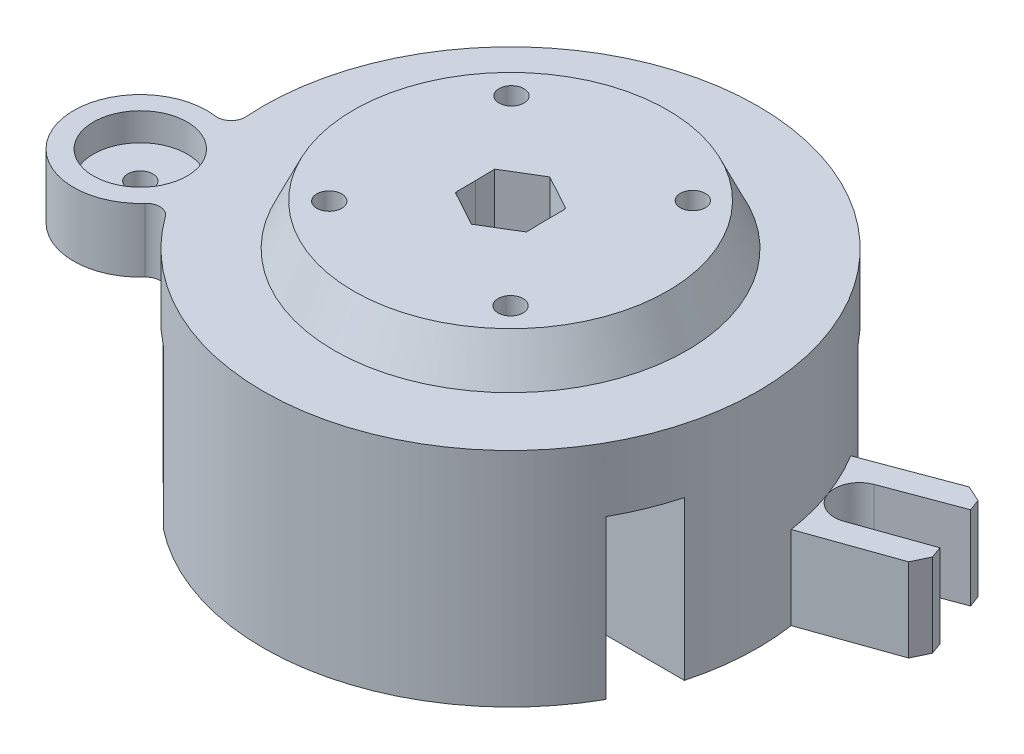
SolidWorks part; units mm, degrees
material "Brass"
ref_plane "Front Plane" through (0, 0, 0) normal (0, 0, 1) x (1, 0, 0)
ref_plane "Top Plane" through (0, 0, 0) normal (0, 1, 0) x (1, 0, 0)
ref_plane "Right Plane" through (0, 0, 0) normal (1, 0, 0) x (0, 0, -1)
sketch "Sketch2" plane through (0, 0, 0) normal (0, 1, 0) x (1, 0, 0)
  line L0 (-400.5493, 0) -> (19626.9166, 0) construction
  line L1 (0, -400.5493) -> (0, 19626.9166) construction
  line L2 (0, 6.35) -> (6.35, 3.4835)
  line L9 (6.35, 3.4835) -> (6.35, -3.4835)
  line L10 (6.35, -3.4835) -> (0, -6.35)
  line L12 (-6.35, -3.4835) -> (0, -6.35)
  line L13 (-6.35, 3.4835) -> (-6.35, -3.4835)
  line L14 (0, 6.35) -> (-6.35, 3.4835)
  circle A0 centre (0, 0) radius 32.258
  circle A1 centre (0, 0) radius 45.212
  point P7 (6.35, 0)
  point P21 (-16.6624, 16.6624)
  point P22 (7.8107, 16.6624)
  point P23 (16.6624, -16.6624)
  point P24 (-16.6624, -16.6624)
  dimension "D1" = 12.7
  dimension "D4" = 64.516
  dimension "D5" = 90.424
  dimension "D2" = 131.41
  dimension "D3" = 12.7
extrude "Boss-Extrude3" add sketch "Sketch2" against normal blind 40.64 contours A1 A0 | A0 L14 L2 L9 L10 L12 L13
sketch "Sketch4" plane through (0, 0, 0) normal (0, 1, 0) x (1, 0, 0)
  circle A0 centre (0, 0) radius 32.258
  dimension "D1" = 64.516
extrude "Boss-Extrude4" add sketch "Sketch4" along normal blind 7.62 draft 25
sketch "Sketch6" plane through (0, -40.64, 0) normal (0, -1, 0) x (-1, 0, 0)
  line L0 (6.35, -3.4835) -> (0, -6.35)
  line L1 (0, -6.35) -> (-6.35, -3.4835)
  line L2 (-6.35, -3.4835) -> (-6.35, 3.4835)
  line L3 (-6.35, 3.4835) -> (0, 6.35)
  line L4 (0, 6.35) -> (6.35, 3.4835)
  line L5 (6.35, 3.4835) -> (6.35, -3.4835)
extrude "Cut-Extrude1" cut sketch "Sketch6" against normal through all
sketch "Sketch7" plane through (0, 7.62, 0) normal (0, 1, 0) x (1, 0, 0)
  line L0 (0, -1000) -> (0, 49000) construction
  line L2 (-1000, 0) -> (49000, 0) construction
  circle A0 centre (-16.4952, 16.6624) radius 2.286
  circle A1 centre (16.6624, 16.6624) radius 2.286
  circle A3 centre (16.6624, -16.6624) radius 2.286
  circle A4 centre (-16.4952, -16.6624) radius 2.286
  point P10 (16.6624, 16.6624)
  point P11 (-16.4952, 16.6624)
  point P12 (16.6624, -16.6624)
  point P13 (-16.4952, -16.6624)
  dimension "D1" = 4.572
  dimension "D2" = 4.572
  dimension "D3" = 4.572
  dimension "D4" = 4.572
extrude "Cut-Extrude2" cut sketch "Sketch7" against normal through all
sketch "Sketch12" plane through (0, 7.62, 0) normal (0, 1, 0) x (1, 0, 0)
  line L0 (0, 0) -> (50000, 0) construction
  line L1 (0, 0) -> (-46984.631, -17101.0072) construction
  circle A0 centre (-49.6458, -18.0696) radius 4.0442
  arc A2 (-47.9736, -5.9928) -> (-40.6021, -26.2461) centre (-49.6458, -18.0696) ccw
  arc A3 (45.212, 0) -> (42.4854, 15.4634) centre (0, 0) ccw
  arc A4 (-36.6585, -26.4628) -> (-40.6021, -26.2461) centre (-38.7179, -27.9495) ccw
  arc A5 (-45.092, -3.2919) -> (-47.9736, -5.9928) centre (-47.6253, -3.4768) cw
  arc A6 (-36.6585, -26.4628) -> (-45.092, -3.2919) centre (0, 0) cw
  arc A7 (-45.212, 0) -> (-45.092, -3.2919) centre (0, 0) ccw
  dimension "D2" = 2.54
  dimension "D1" = 20
  dimension "D3" = 52.832
extrude "Boss-Extrude8" add sketch "Sketch12" against normal blind 11.684 from surface at -7.62 contours A4 A6 A5 A2 A0
sketch "Sketch16" plane through (0, 0, 0) normal (0, 1, 0) x (1, 0, 0)
  circle A0 centre (-49.6458, -18.0696) radius 3.175
sketch "Sketch18" plane through (0, 0, 0) normal (0, 1, 0) x (1, 0, 0)
  circle A1 centre (-49.6458, -18.0696) radius 8.5673
  dimension "D1" = 17.1345
extrude "Cut-Extrude3" cut sketch "Sketch18" against normal blind 5.08
sketch "Sketch19" plane through (0, -5.08, 0) normal (0, 1, 0) x (1, 0, 0)
  circle A1 centre (-49.6458, -18.0696) radius 2.286
  dimension "D1" = 4.572
extrude "Cut-Extrude4" cut sketch "Sketch19" against normal through all
sketch "Sketch20" plane through (0, -40.64, 0) normal (0, -1, 0) x (1, 0, 0)
  line L0 (-5.0709, 1.8457) -> (-46989.7019, 17102.8528) construction
  line L1 (48.3078, -12.7174) -> (61.2371, -17.2959)
  line L2 (61.2371, -17.2959) -> (62.0002, -15.141)
  line L3 (62.0002, -15.141) -> (60.6019, -12.2094)
  line L4 (60.6019, -12.2094) -> (44.7293, -6.5887)
  line L5 (45.1805, -21.3096) -> (58.0279, -26.113)
  line L6 (58.0279, -26.113) -> (57.2273, -28.2543)
  line L7 (57.2273, -28.2543) -> (54.2718, -29.6012)
  line L8 (54.2718, -29.6012) -> (38.4998, -23.7043)
  arc A0 (48.3078, -12.7174) -> (45.1805, -21.3096) centre (46.7817, -17.0271) ccw
  circle A1 centre (0, 0) radius 45.212 construction
  arc A2 (38.4998, -23.7043) -> (44.7293, -6.5887) centre (0, 0) ccw
  circle M5 centre (0, 0) radius 45.212
  dimension "D1" = 4.572
  dimension "D3" = 13.716
  dimension "D2" = 49.784
  dimension "D4" = 1
  dimension "D5" = 45
extrude "Boss-Extrude9" add sketch "Sketch20" against normal blind 15.24 contours A0 L1 L2 L3 L4 M5 | A0 L8 L7 L6 L5 M5
sketch "Sketch21" plane through (0, -40.64, 0) normal (0, -1, 0) x (1, 0, 0)
  line L0 (16.6624, 6.5024) -> (26.8224, 6.5024)
  line L1 (16.6624, -983.3376) -> (16.6624, 49016.6624) construction
  line L2 (26.8224, 6.5024) -> (26.8224, 11.8441)
  line L3 (26.8224, 11.8441) -> (43.633, 11.8441)
  line L4 (16.6624, 26.8224) -> (25.3049, 26.8224)
  line L5 (25.3049, 26.8224) -> (25.3049, 22.0041)
  line L6 (25.3049, 22.0041) -> (39.4962, 22.0041)
  line L7 (-16.4952, 16.6624) -> (-35371.8343, -35338.6767) construction
  line L8 (-23.6794, 9.4782) -> (-30.8636, 16.6624)
  line L9 (-30.8636, 16.6624) -> (-27.2715, 20.2545)
  line L10 (-27.2715, 20.2545) -> (-35.2851, 28.2681)
  line L11 (-9.311, 23.8466) -> (-16.4952, 31.0308)
  line L12 (-16.4952, 31.0308) -> (-20.0873, 27.4387)
  line L13 (-20.0873, 27.4387) -> (-28.082, 35.4334)
  arc A0 (-23.6794, 9.4782) -> (-9.311, 23.8466) centre (-16.4952, 16.6624) ccw
  arc A1 (16.6624, 26.8224) -> (16.6624, 6.5024) centre (16.6624, 16.6624) ccw
  arc A2 (-45.092, 3.2919) -> (-36.6585, 26.4628) centre (0, 0) ccw construction
  arc A3 (43.633, 11.8441) -> (39.4962, 22.0041) centre (0, 0) ccw
  arc A4 (-28.082, 35.4334) -> (-35.2851, 28.2681) centre (0, 0) ccw
  arc A5 (14.6222, 42.7822) -> (10.7562, 43.9139) centre (0, 0) ccw
  point P4 (26.8224, 9.1732)
  circle M1 centre (-16.4952, 16.6624) radius 2.286
  circle M2 centre (16.6624, 16.6624) radius 2.286
  arc M5 (44.7293, -6.5887) -> (38.4998, -23.7043) centre (0, 0) ccw
  dimension "D1" = 10.16
  dimension "D2" = 10.16
  dimension "D6" = 10.16
  dimension "D3" = 10.16
  dimension "D4" = 8.6425
  dimension "D5" = 10.16
  dimension "D7" = 10.16
extrude "Cut-Extrude5" cut sketch "Sketch21" against normal blind 28.956 contours L8 A0 L11 L12 L13 L10 L9 M5 M1 | L4 A1 L0 L2 L3 L6 L5 M5 M2
pattern_circular "CirPattern1" count 2 over 360 about axis through (0, 0, 0) along (0, 1, 0) of "Cut-Extrude5"
sketch "Sketch22" plane through (0, 7.62, 0) normal (0, 1, 0) x (1, 0, 0)
  line L3 (6.4286, -3.5266) -> (6.2684, 3.804)
  line L4 (6.2684, 3.804) -> (-0.1602, 7.3306)
  line L5 (-0.1602, 7.3306) -> (-6.4286, 3.5266)
  line L6 (-6.4286, 3.5266) -> (-6.2684, -3.804)
  line L7 (-6.2684, -3.804) -> (0.1602, -7.3306)
  line L8 (0.1602, -7.3306) -> (6.4286, -3.5266)
  circle A0 centre (0, 0) radius 6.35 construction
  dimension "D1" = 12.7
extrude "Cut-Extrude6" cut sketch "Sketch22" against normal through all contours L3 L4 L5 L6 L7 L8
